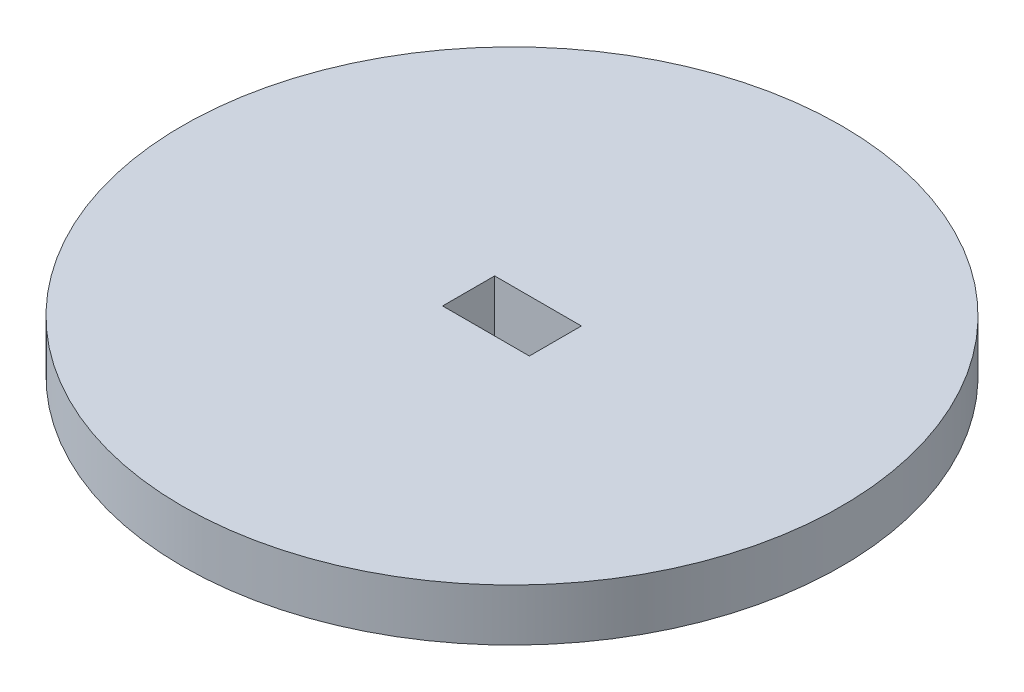
SolidWorks part; units mm, degrees
ref_plane "Plano frontal" through (0, 0, 0) normal (0, 0, 1) x (1, 0, 0)
ref_plane "Plano superior" through (0, 0, 0) normal (0, 1, 0) x (1, 0, 0)
ref_plane "Plano direito" through (0, 0, 0) normal (1, 0, 0) x (0, 0, -1)
sketch "Esboço1" plane through (0, 0, 0) normal (0, 1, 0) x (1, 0, 0)
  circle A0 centre (0, 0) radius 38
  dimension "D1" = 76
extrude "Ressalto-extrusão1" add sketch "Esboço1" along normal blind 6
sketch "Esboço5" plane through (0, 6, 0) normal (0, 1, 0) x (1, 0, 0)
  line L1 (5, -3) -> (-5, -3)
  line L2 (5, -3) -> (5, 3)
  line L3 (5, 3) -> (-5, 3)
  line L4 (-5, -3) -> (-5, 3)
  line L5 (5, -3) -> (-5, 3) construction
  line L6 (5, 3) -> (-5, -3) construction
  point P0 (0, 0)
  dimension "D1" = 10
  dimension "D2" = 6
extrude "Corte-extrusão1" cut sketch "Esboço5" against normal blind 6
